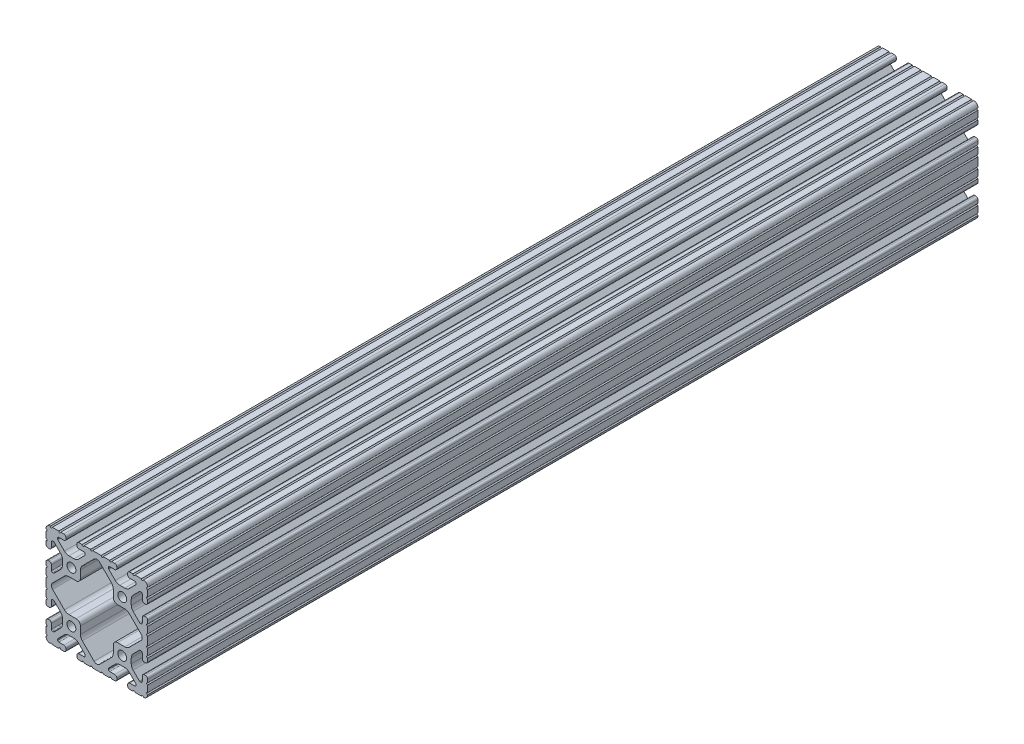
SolidWorks part; units mm, degrees
material "6105-T5 Aluminum"
ref_plane "Front Plane" through (0, 0, 0) normal (0, 0, 1) x (1, 0, 0)
ref_plane "Top Plane" through (0, 0, 0) normal (0, 1, 0) x (1, 0, 0)
ref_plane "Right Plane" through (0, 0, 0) normal (1, 0, 0) x (0, 0, -1)
sketch "Sketch1" plane through (0, 0, 0) normal (0, 0, 1) x (1, 0, 0)
  line L0 (15.487, 12.312) -> (20.9469, 12.312)
  line L1 (24.3055, 10.9208) -> (33.1609, 2.0655)
  line L2 (33.1609, -2.0655) -> (24.3055, -10.9208)
  line L3 (20.9469, -12.312) -> (15.487, -12.312)
  line L4 (12.312, -15.487) -> (12.312, -20.9469)
  line L5 (10.9208, -24.3055) -> (2.0655, -33.1609)
  line L6 (-2.0655, -33.1609) -> (-10.9208, -24.3055)
  line L7 (-12.312, -20.9469) -> (-12.312, -15.487)
  line L8 (-15.487, -12.312) -> (-20.9469, -12.312)
  line L9 (-24.3055, -10.9208) -> (-33.1609, -2.0655)
  line L10 (-33.1609, 2.0655) -> (-24.3055, 10.9208)
  line L11 (-20.9469, 12.312) -> (-15.487, 12.312)
  line L12 (-12.312, 15.487) -> (-12.312, 20.9469)
  line L13 (-10.9208, 24.3055) -> (-2.0655, 33.1609)
  line L14 (2.0655, 33.1609) -> (10.9208, 24.3055)
  line L15 (12.312, 20.9469) -> (12.312, 15.487)
  line L16 (-38.1, 3.2004) -> (-38.1, -3.2004)
  line L17 (-38.1, -4.7244) -> (-38.1, -9.5504)
  line L18 (-38.1, -11.0744) -> (-38.1, -13.4112)
  line L19 (-36.5252, -14.986) -> (-35.6108, -14.986)
  line L20 (-34.036, -13.4112) -> (-34.036, -9.652)
  line L21 (-33.147, -8.763) -> (-32.5789, -8.763)
  line L22 (-31.9503, -9.0234) -> (-27.1792, -13.7945)
  line L23 (-25.788, -17.1531) -> (-25.788, -20.9469)
  line L24 (-27.1792, -24.3055) -> (-31.9503, -29.0766)
  line L25 (-32.5789, -29.337) -> (-33.147, -29.337)
  line L26 (-34.036, -28.448) -> (-34.036, -24.6888)
  line L27 (-35.6108, -23.114) -> (-36.5252, -23.114)
  line L28 (-38.1, -24.6888) -> (-38.1, -27.0256)
  line L29 (-38.1, -28.5496) -> (-38.1, -33.3756)
  line L30 (-38.1, -34.8996) -> (-38.1, -34.925)
  line L31 (-34.925, -38.1) -> (-34.8996, -38.1)
  line L32 (-33.3756, -38.1) -> (-28.5496, -38.1)
  line L33 (-27.0256, -38.1) -> (-24.6888, -38.1)
  line L34 (-23.114, -36.5252) -> (-23.114, -35.6108)
  line L35 (-24.6888, -34.036) -> (-28.448, -34.036)
  line L36 (-29.337, -33.147) -> (-29.337, -32.5789)
  line L37 (-29.0766, -31.9503) -> (-24.3055, -27.1792)
  line L38 (-20.9469, -25.788) -> (-17.1531, -25.788)
  line L39 (-13.7945, -27.1792) -> (-9.0234, -31.9503)
  line L40 (-8.763, -32.5789) -> (-8.763, -33.147)
  line L41 (-9.652, -34.036) -> (-13.4112, -34.036)
  line L42 (-14.986, -35.6108) -> (-14.986, -36.5252)
  line L43 (-13.4112, -38.1) -> (-11.0744, -38.1)
  line L44 (-9.5504, -38.1) -> (-4.7244, -38.1)
  line L45 (-3.2004, -38.1) -> (3.2004, -38.1)
  line L46 (4.7244, -38.1) -> (9.5504, -38.1)
  line L47 (11.0744, -38.1) -> (13.4112, -38.1)
  line L48 (14.986, -36.5252) -> (14.986, -35.6108)
  line L49 (13.4112, -34.036) -> (9.652, -34.036)
  line L50 (8.763, -33.147) -> (8.763, -32.5789)
  line L51 (9.0234, -31.9503) -> (13.7945, -27.1792)
  line L52 (17.1531, -25.788) -> (20.9469, -25.788)
  line L53 (24.3055, -27.1792) -> (29.0766, -31.9503)
  line L54 (29.337, -32.5789) -> (29.337, -33.147)
  line L55 (28.448, -34.036) -> (24.6888, -34.036)
  line L56 (23.114, -35.6108) -> (23.114, -36.5252)
  line L57 (24.6888, -38.1) -> (27.0256, -38.1)
  line L58 (28.5496, -38.1) -> (33.3756, -38.1)
  line L59 (34.8996, -38.1) -> (34.925, -38.1)
  line L60 (38.1, -34.925) -> (38.1, -34.8996)
  line L61 (38.1, -33.3756) -> (38.1, -28.5496)
  line L62 (38.1, -27.0256) -> (38.1, -24.6888)
  line L63 (36.5252, -23.114) -> (35.6108, -23.114)
  line L64 (34.036, -24.6888) -> (34.036, -28.448)
  line L65 (33.147, -29.337) -> (32.5789, -29.337)
  line L66 (31.9503, -29.0766) -> (27.1792, -24.3055)
  line L67 (25.788, -20.9469) -> (25.788, -17.1531)
  line L68 (27.1792, -13.7945) -> (31.9503, -9.0234)
  line L69 (32.5789, -8.763) -> (33.147, -8.763)
  line L70 (34.036, -9.652) -> (34.036, -13.4112)
  line L71 (35.6108, -14.986) -> (36.5252, -14.986)
  line L72 (38.1, -13.4112) -> (38.1, -11.0744)
  line L73 (38.1, -9.5504) -> (38.1, -4.7244)
  line L74 (38.1, -3.2004) -> (38.1, 3.2004)
  line L75 (38.1, 4.7244) -> (38.1, 9.5504)
  line L76 (38.1, 11.0744) -> (38.1, 13.4112)
  line L77 (36.5252, 14.986) -> (35.6108, 14.986)
  line L78 (34.036, 13.4112) -> (34.036, 9.652)
  line L79 (33.147, 8.763) -> (32.5789, 8.763)
  line L80 (31.9503, 9.0234) -> (27.1792, 13.7945)
  line L81 (25.788, 17.1531) -> (25.788, 20.9469)
  line L82 (27.1792, 24.3055) -> (31.9503, 29.0766)
  line L83 (32.5789, 29.337) -> (33.147, 29.337)
  line L84 (34.036, 28.448) -> (34.036, 24.6888)
  line L85 (35.6108, 23.114) -> (36.5252, 23.114)
  line L86 (38.1, 24.6888) -> (38.1, 27.0256)
  line L87 (38.1, 28.5496) -> (38.1, 33.3756)
  line L88 (38.1, 34.8996) -> (38.1, 34.925)
  line L89 (34.925, 38.1) -> (34.8996, 38.1)
  line L90 (33.3756, 38.1) -> (28.5496, 38.1)
  line L91 (27.0256, 38.1) -> (24.6888, 38.1)
  line L92 (23.114, 36.5252) -> (23.114, 35.6108)
  line L93 (24.6888, 34.036) -> (28.448, 34.036)
  line L94 (29.337, 33.147) -> (29.337, 32.5789)
  line L95 (29.0766, 31.9503) -> (24.3055, 27.1792)
  line L96 (20.9469, 25.788) -> (17.1531, 25.788)
  line L97 (13.7945, 27.1792) -> (9.0234, 31.9503)
  line L98 (8.763, 32.5789) -> (8.763, 33.147)
  line L99 (9.652, 34.036) -> (13.4112, 34.036)
  line L100 (14.986, 35.6108) -> (14.986, 36.5252)
  line L101 (13.4112, 38.1) -> (11.0744, 38.1)
  line L102 (9.5504, 38.1) -> (4.7244, 38.1)
  line L103 (3.2004, 38.1) -> (-3.2004, 38.1)
  line L104 (-4.7244, 38.1) -> (-9.5504, 38.1)
  line L105 (-11.0744, 38.1) -> (-13.4112, 38.1)
  line L106 (-14.986, 36.5252) -> (-14.986, 35.6108)
  line L107 (-13.4112, 34.036) -> (-9.652, 34.036)
  line L108 (-8.763, 33.147) -> (-8.763, 32.5789)
  line L109 (-9.0234, 31.9503) -> (-13.7945, 27.1792)
  line L110 (-17.1531, 25.788) -> (-20.9469, 25.788)
  line L111 (-24.3055, 27.1792) -> (-29.0766, 31.9503)
  line L112 (-29.337, 32.5789) -> (-29.337, 33.147)
  line L113 (-28.448, 34.036) -> (-24.6888, 34.036)
  line L114 (-23.114, 35.6108) -> (-23.114, 36.5252)
  line L115 (-24.6888, 38.1) -> (-27.0256, 38.1)
  line L116 (-28.5496, 38.1) -> (-33.3756, 38.1)
  line L117 (-34.8996, 38.1) -> (-34.925, 38.1)
  line L118 (-38.1, 34.925) -> (-38.1, 34.8996)
  line L119 (-38.1, 33.3756) -> (-38.1, 28.5496)
  line L120 (-38.1, 27.0256) -> (-38.1, 24.6888)
  line L121 (-36.5252, 23.114) -> (-35.6108, 23.114)
  line L122 (-34.036, 24.6888) -> (-34.036, 28.448)
  line L123 (-33.147, 29.337) -> (-32.5789, 29.337)
  line L124 (-31.9503, 29.0766) -> (-27.1792, 24.3055)
  line L125 (-25.788, 20.9469) -> (-25.788, 17.1531)
  line L126 (-27.1792, 13.7945) -> (-31.9503, 9.0234)
  line L127 (-32.5789, 8.763) -> (-33.147, 8.763)
  line L128 (-34.036, 9.652) -> (-34.036, 13.4112)
  line L129 (-35.6108, 14.986) -> (-36.5252, 14.986)
  line L130 (-38.1, 13.4112) -> (-38.1, 11.0744)
  line L131 (-38.1, 9.5504) -> (-38.1, 4.7244)
  circle A0 centre (-19.05, 19.05) radius 3.3274
  circle A1 centre (-19.05, -19.05) radius 3.3274
  circle A2 centre (19.05, -19.05) radius 3.3274
  circle A3 centre (19.05, 19.05) radius 3.3274
  arc A4 (12.312, 15.487) -> (15.487, 12.312) centre (15.487, 15.487) ccw
  arc A5 (24.3055, 10.9208) -> (20.9469, 12.312) centre (20.9469, 7.5622) ccw
  arc A6 (33.1609, -2.0655) -> (33.1609, 2.0655) centre (31.0954, 0) ccw
  arc A7 (20.9469, -12.312) -> (24.3055, -10.9208) centre (20.9469, -7.5622) ccw
  arc A8 (15.487, -12.312) -> (12.312, -15.487) centre (15.487, -15.487) ccw
  arc A9 (10.9208, -24.3055) -> (12.312, -20.9469) centre (7.5622, -20.9469) ccw
  arc A10 (-2.0655, -33.1609) -> (2.0655, -33.1609) centre (0, -31.0954) ccw
  arc A11 (-12.312, -20.9469) -> (-10.9208, -24.3055) centre (-7.5622, -20.9469) ccw
  arc A12 (-12.312, -15.487) -> (-15.487, -12.312) centre (-15.487, -15.487) ccw
  arc A13 (-24.3055, -10.9208) -> (-20.9469, -12.312) centre (-20.9469, -7.5622) ccw
  arc A14 (-33.1609, 2.0655) -> (-33.1609, -2.0655) centre (-31.0954, 0) ccw
  arc A15 (-20.9469, 12.312) -> (-24.3055, 10.9208) centre (-20.9469, 7.5622) ccw
  arc A16 (-15.487, 12.312) -> (-12.312, 15.487) centre (-15.487, 15.487) ccw
  arc A17 (-10.9208, 24.3055) -> (-12.312, 20.9469) centre (-7.5622, 20.9469) ccw
  arc A18 (2.0655, 33.1609) -> (-2.0655, 33.1609) centre (0, 31.0954) ccw
  arc A19 (12.312, 20.9469) -> (10.9208, 24.3055) centre (7.5622, 20.9469) ccw
  arc A20 (-38.1, -4.7244) -> (-38.1, -3.2004) centre (-38.1, -3.9624) ccw
  arc A21 (-38.1, -11.0744) -> (-38.1, -9.5504) centre (-38.1, -10.3124) ccw
  arc A22 (-38.1, -13.4112) -> (-36.5252, -14.986) centre (-36.5252, -13.4112) ccw
  arc A23 (-35.6108, -14.986) -> (-34.036, -13.4112) centre (-35.6108, -13.4112) ccw
  arc A24 (-33.147, -8.763) -> (-34.036, -9.652) centre (-33.147, -9.652) ccw
  arc A25 (-31.9503, -9.0234) -> (-32.5789, -8.763) centre (-32.5789, -9.652) ccw
  arc A26 (-25.788, -17.1531) -> (-27.1792, -13.7945) centre (-30.5378, -17.1531) ccw
  arc A27 (-27.1792, -24.3055) -> (-25.788, -20.9469) centre (-30.5378, -20.9469) ccw
  arc A28 (-32.5789, -29.337) -> (-31.9503, -29.0766) centre (-32.5789, -28.448) ccw
  arc A29 (-34.036, -28.448) -> (-33.147, -29.337) centre (-33.147, -28.448) ccw
  arc A30 (-34.036, -24.6888) -> (-35.6108, -23.114) centre (-35.6108, -24.6888) ccw
  arc A31 (-36.5252, -23.114) -> (-38.1, -24.6888) centre (-36.5252, -24.6888) ccw
  arc A32 (-38.1, -28.5496) -> (-38.1, -27.0256) centre (-38.1, -27.7876) ccw
  arc A33 (-38.1, -34.8996) -> (-38.1, -33.3756) centre (-38.1, -34.1376) ccw
  arc A34 (-38.1, -34.925) -> (-34.925, -38.1) centre (-34.925, -34.925) ccw
  arc A35 (-33.3756, -38.1) -> (-34.8996, -38.1) centre (-34.1376, -38.1) ccw
  arc A36 (-27.0256, -38.1) -> (-28.5496, -38.1) centre (-27.7876, -38.1) ccw
  arc A37 (-24.6888, -38.1) -> (-23.114, -36.5252) centre (-24.6888, -36.5252) ccw
  arc A38 (-23.114, -35.6108) -> (-24.6888, -34.036) centre (-24.6888, -35.6108) ccw
  arc A39 (-29.337, -33.147) -> (-28.448, -34.036) centre (-28.448, -33.147) ccw
  arc A40 (-29.0766, -31.9503) -> (-29.337, -32.5789) centre (-28.448, -32.5789) ccw
  arc A41 (-20.9469, -25.788) -> (-24.3055, -27.1792) centre (-20.9469, -30.5378) ccw
  arc A42 (-13.7945, -27.1792) -> (-17.1531, -25.788) centre (-17.1531, -30.5378) ccw
  arc A43 (-8.763, -32.5789) -> (-9.0234, -31.9503) centre (-9.652, -32.5789) ccw
  arc A44 (-9.652, -34.036) -> (-8.763, -33.147) centre (-9.652, -33.147) ccw
  arc A45 (-13.4112, -34.036) -> (-14.986, -35.6108) centre (-13.4112, -35.6108) ccw
  arc A46 (-14.986, -36.5252) -> (-13.4112, -38.1) centre (-13.4112, -36.5252) ccw
  arc A47 (-9.5504, -38.1) -> (-11.0744, -38.1) centre (-10.3124, -38.1) ccw
  arc A48 (-3.2004, -38.1) -> (-4.7244, -38.1) centre (-3.9624, -38.1) ccw
  arc A49 (4.7244, -38.1) -> (3.2004, -38.1) centre (3.9624, -38.1) ccw
  arc A50 (11.0744, -38.1) -> (9.5504, -38.1) centre (10.3124, -38.1) ccw
  arc A51 (13.4112, -38.1) -> (14.986, -36.5252) centre (13.4112, -36.5252) ccw
  arc A52 (14.986, -35.6108) -> (13.4112, -34.036) centre (13.4112, -35.6108) ccw
  arc A53 (8.763, -33.147) -> (9.652, -34.036) centre (9.652, -33.147) ccw
  arc A54 (9.0234, -31.9503) -> (8.763, -32.5789) centre (9.652, -32.5789) ccw
  arc A55 (17.1531, -25.788) -> (13.7945, -27.1792) centre (17.1531, -30.5378) ccw
  arc A56 (24.3055, -27.1792) -> (20.9469, -25.788) centre (20.9469, -30.5378) ccw
  arc A57 (29.337, -32.5789) -> (29.0766, -31.9503) centre (28.448, -32.5789) ccw
  arc A58 (28.448, -34.036) -> (29.337, -33.147) centre (28.448, -33.147) ccw
  arc A59 (24.6888, -34.036) -> (23.114, -35.6108) centre (24.6888, -35.6108) ccw
  arc A60 (23.114, -36.5252) -> (24.6888, -38.1) centre (24.6888, -36.5252) ccw
  arc A61 (28.5496, -38.1) -> (27.0256, -38.1) centre (27.7876, -38.1) ccw
  arc A62 (34.8996, -38.1) -> (33.3756, -38.1) centre (34.1376, -38.1) ccw
  arc A63 (34.925, -38.1) -> (38.1, -34.925) centre (34.925, -34.925) ccw
  arc A64 (38.1, -33.3756) -> (38.1, -34.8996) centre (38.1, -34.1376) ccw
  arc A65 (38.1, -27.0256) -> (38.1, -28.5496) centre (38.1, -27.7876) ccw
  arc A66 (38.1, -24.6888) -> (36.5252, -23.114) centre (36.5252, -24.6888) ccw
  arc A67 (35.6108, -23.114) -> (34.036, -24.6888) centre (35.6108, -24.6888) ccw
  arc A68 (33.147, -29.337) -> (34.036, -28.448) centre (33.147, -28.448) ccw
  arc A69 (31.9503, -29.0766) -> (32.5789, -29.337) centre (32.5789, -28.448) ccw
  arc A70 (25.788, -20.9469) -> (27.1792, -24.3055) centre (30.5378, -20.9469) ccw
  arc A71 (27.1792, -13.7945) -> (25.788, -17.1531) centre (30.5378, -17.1531) ccw
  arc A72 (32.5789, -8.763) -> (31.9503, -9.0234) centre (32.5789, -9.652) ccw
  arc A73 (34.036, -9.652) -> (33.147, -8.763) centre (33.147, -9.652) ccw
  arc A74 (34.036, -13.4112) -> (35.6108, -14.986) centre (35.6108, -13.4112) ccw
  arc A75 (36.5252, -14.986) -> (38.1, -13.4112) centre (36.5252, -13.4112) ccw
  arc A76 (38.1, -9.5504) -> (38.1, -11.0744) centre (38.1, -10.3124) ccw
  arc A77 (38.1, -3.2004) -> (38.1, -4.7244) centre (38.1, -3.9624) ccw
  arc A78 (38.1, 4.7244) -> (38.1, 3.2004) centre (38.1, 3.9624) ccw
  arc A79 (38.1, 11.0744) -> (38.1, 9.5504) centre (38.1, 10.3124) ccw
  arc A80 (38.1, 13.4112) -> (36.5252, 14.986) centre (36.5252, 13.4112) ccw
  arc A81 (35.6108, 14.986) -> (34.036, 13.4112) centre (35.6108, 13.4112) ccw
  arc A82 (33.147, 8.763) -> (34.036, 9.652) centre (33.147, 9.652) ccw
  arc A83 (31.9503, 9.0234) -> (32.5789, 8.763) centre (32.5789, 9.652) ccw
  arc A84 (25.788, 17.1531) -> (27.1792, 13.7945) centre (30.5378, 17.1531) ccw
  arc A85 (27.1792, 24.3055) -> (25.788, 20.9469) centre (30.5378, 20.9469) ccw
  arc A86 (32.5789, 29.337) -> (31.9503, 29.0766) centre (32.5789, 28.448) ccw
  arc A87 (34.036, 28.448) -> (33.147, 29.337) centre (33.147, 28.448) ccw
  arc A88 (34.036, 24.6888) -> (35.6108, 23.114) centre (35.6108, 24.6888) ccw
  arc A89 (36.5252, 23.114) -> (38.1, 24.6888) centre (36.5252, 24.6888) ccw
  arc A90 (38.1, 28.5496) -> (38.1, 27.0256) centre (38.1, 27.7876) ccw
  arc A91 (38.1, 34.8996) -> (38.1, 33.3756) centre (38.1, 34.1376) ccw
  arc A92 (38.1, 34.925) -> (34.925, 38.1) centre (34.925, 34.925) ccw
  arc A93 (33.3756, 38.1) -> (34.8996, 38.1) centre (34.1376, 38.1) ccw
  arc A94 (27.0256, 38.1) -> (28.5496, 38.1) centre (27.7876, 38.1) ccw
  arc A95 (24.6888, 38.1) -> (23.114, 36.5252) centre (24.6888, 36.5252) ccw
  arc A96 (23.114, 35.6108) -> (24.6888, 34.036) centre (24.6888, 35.6108) ccw
  arc A97 (29.337, 33.147) -> (28.448, 34.036) centre (28.448, 33.147) ccw
  arc A98 (29.0766, 31.9503) -> (29.337, 32.5789) centre (28.448, 32.5789) ccw
  arc A99 (20.9469, 25.788) -> (24.3055, 27.1792) centre (20.9469, 30.5378) ccw
  arc A100 (13.7945, 27.1792) -> (17.1531, 25.788) centre (17.1531, 30.5378) ccw
  arc A101 (8.763, 32.5789) -> (9.0234, 31.9503) centre (9.652, 32.5789) ccw
  arc A102 (9.652, 34.036) -> (8.763, 33.147) centre (9.652, 33.147) ccw
  arc A103 (13.4112, 34.036) -> (14.986, 35.6108) centre (13.4112, 35.6108) ccw
  arc A104 (14.986, 36.5252) -> (13.4112, 38.1) centre (13.4112, 36.5252) ccw
  arc A105 (9.5504, 38.1) -> (11.0744, 38.1) centre (10.3124, 38.1) ccw
  arc A106 (3.2004, 38.1) -> (4.7244, 38.1) centre (3.9624, 38.1) ccw
  arc A107 (-4.7244, 38.1) -> (-3.2004, 38.1) centre (-3.9624, 38.1) ccw
  arc A108 (-11.0744, 38.1) -> (-9.5504, 38.1) centre (-10.3124, 38.1) ccw
  arc A109 (-13.4112, 38.1) -> (-14.986, 36.5252) centre (-13.4112, 36.5252) ccw
  arc A110 (-14.986, 35.6108) -> (-13.4112, 34.036) centre (-13.4112, 35.6108) ccw
  arc A111 (-8.763, 33.147) -> (-9.652, 34.036) centre (-9.652, 33.147) ccw
  arc A112 (-9.0234, 31.9503) -> (-8.763, 32.5789) centre (-9.652, 32.5789) ccw
  arc A113 (-17.1531, 25.788) -> (-13.7945, 27.1792) centre (-17.1531, 30.5378) ccw
  arc A114 (-24.3055, 27.1792) -> (-20.9469, 25.788) centre (-20.9469, 30.5378) ccw
  arc A115 (-29.337, 32.5789) -> (-29.0766, 31.9503) centre (-28.448, 32.5789) ccw
  arc A116 (-28.448, 34.036) -> (-29.337, 33.147) centre (-28.448, 33.147) ccw
  arc A117 (-24.6888, 34.036) -> (-23.114, 35.6108) centre (-24.6888, 35.6108) ccw
  arc A118 (-23.114, 36.5252) -> (-24.6888, 38.1) centre (-24.6888, 36.5252) ccw
  arc A119 (-28.5496, 38.1) -> (-27.0256, 38.1) centre (-27.7876, 38.1) ccw
  arc A120 (-34.8996, 38.1) -> (-33.3756, 38.1) centre (-34.1376, 38.1) ccw
  arc A121 (-34.925, 38.1) -> (-38.1, 34.925) centre (-34.925, 34.925) ccw
  arc A122 (-38.1, 33.3756) -> (-38.1, 34.8996) centre (-38.1, 34.1376) ccw
  arc A123 (-38.1, 27.0256) -> (-38.1, 28.5496) centre (-38.1, 27.7876) ccw
  arc A124 (-38.1, 24.6888) -> (-36.5252, 23.114) centre (-36.5252, 24.6888) ccw
  arc A125 (-35.6108, 23.114) -> (-34.036, 24.6888) centre (-35.6108, 24.6888) ccw
  arc A126 (-33.147, 29.337) -> (-34.036, 28.448) centre (-33.147, 28.448) ccw
  arc A127 (-31.9503, 29.0766) -> (-32.5789, 29.337) centre (-32.5789, 28.448) ccw
  arc A128 (-25.788, 20.9469) -> (-27.1792, 24.3055) centre (-30.5378, 20.9469) ccw
  arc A129 (-27.1792, 13.7945) -> (-25.788, 17.1531) centre (-30.5378, 17.1531) ccw
  arc A130 (-32.5789, 8.763) -> (-31.9503, 9.0234) centre (-32.5789, 9.652) ccw
  arc A131 (-34.036, 9.652) -> (-33.147, 8.763) centre (-33.147, 9.652) ccw
  arc A132 (-34.036, 13.4112) -> (-35.6108, 14.986) centre (-35.6108, 13.4112) ccw
  arc A133 (-36.5252, 14.986) -> (-38.1, 13.4112) centre (-36.5252, 13.4112) ccw
  arc A134 (-38.1, 9.5504) -> (-38.1, 11.0744) centre (-38.1, 10.3124) ccw
  arc A135 (-38.1, 3.2004) -> (-38.1, 4.7244) centre (-38.1, 3.9624) ccw
  dimension "D1" = 19.05
  dimension "D2" = 19.05
  dimension "D3" = 19.05
  dimension "D4" = 19.05
extrude "Boss-Extrude1" add sketch "Sketch1" along normal blind 622.3
